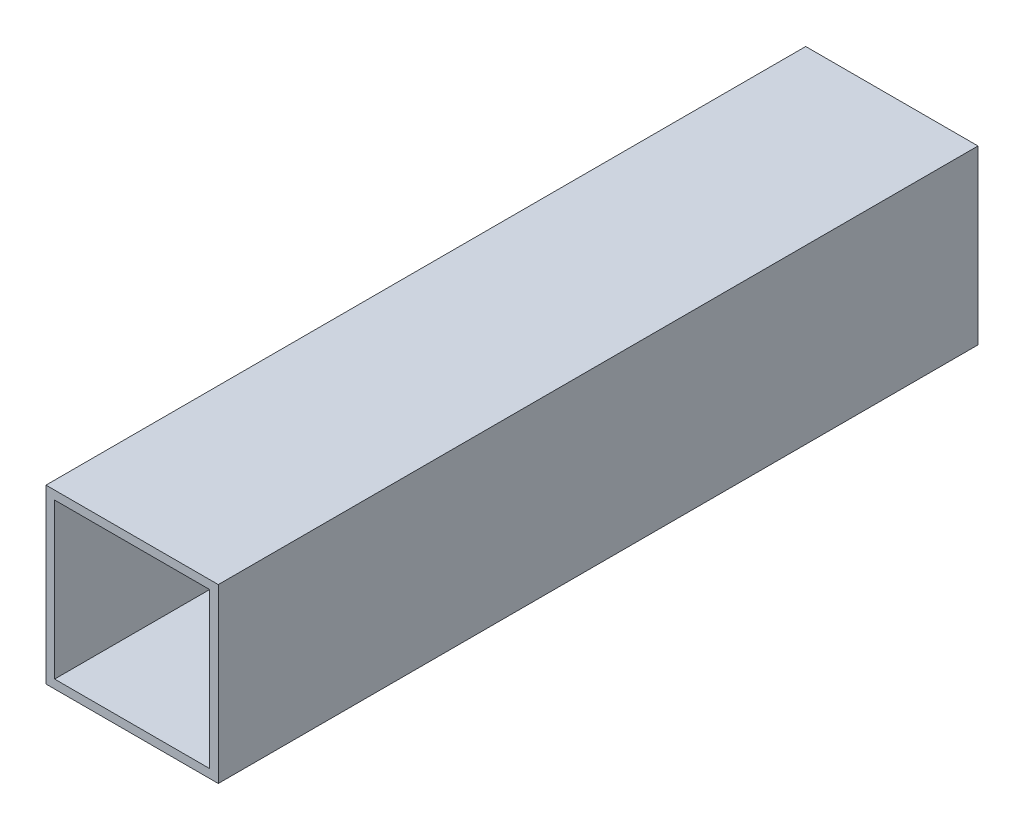
SolidWorks part; units mm, degrees
ref_plane "Front Plane" through (0, 0, 0) normal (0, 0, 1) x (1, 0, 0)
ref_plane "Top Plane" through (0, 0, 0) normal (0, 1, 0) x (1, 0, 0)
ref_plane "Right Plane" through (0, 0, 0) normal (1, 0, 0) x (0, 0, -1)
sketch "Sketch1" plane through (0, 0, 0) normal (0, 0, 1) x (1, 0, 0)
  line L5 (-15.875, 15.875) -> (15.875, 15.875)
  line L6 (-15.875, 15.875) -> (-15.875, -15.875)
  line L11 (-15.875, -15.875) -> (15.875, -15.875)
  line L12 (15.875, 15.875) -> (15.875, -15.875)
  line L13 (-15.875, 15.875) -> (15.875, -15.875) construction
  line L14 (-15.875, -15.875) -> (15.875, 15.875) construction
  line L15 (-14.2875, 14.2875) -> (14.2875, 14.2875)
  line L16 (-14.2875, 14.2875) -> (-14.2875, -14.2875)
  line L17 (-14.2875, -14.2875) -> (14.2875, -14.2875)
  line L18 (14.2875, 14.2875) -> (14.2875, -14.2875)
  line L19 (-14.2875, 14.2875) -> (14.2875, -14.2875) construction
  line L20 (-14.2875, -14.2875) -> (14.2875, 14.2875) construction
  point P0 (0, 0)
  point P6 (0, 0)
  dimension "D1" = 31.75
  dimension "D2" = 31.75
  dimension "D3" = 1.5875
extrude "Boss-Extrude1" add sketch "Sketch1" along normal blind 140
